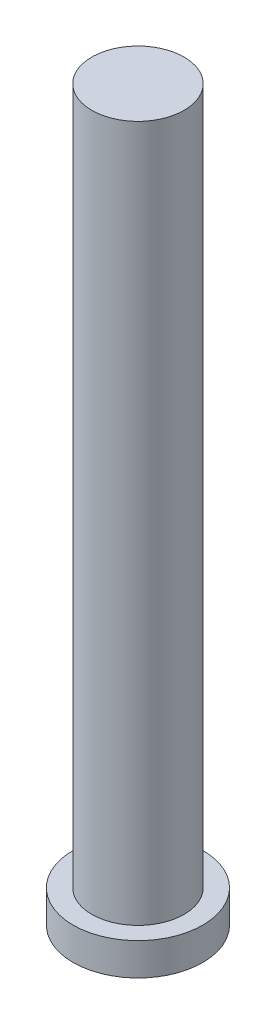
SolidWorks part; units mm, degrees
ref_plane "Front Plane" through (0, 0, 0) normal (0, 0, 1) x (1, 0, 0)
ref_plane "Top Plane" through (0, 0, 0) normal (0, 1, 0) x (1, 0, 0)
ref_plane "Right Plane" through (0, 0, 0) normal (1, 0, 0) x (0, 0, -1)
sketch "Sketch1" plane through (0, 0, 0) normal (0, 1, 0) x (1, 0, 0)
  circle A0 centre (0, 0) radius 4
extrude "Boss-Extrude1" add sketch "Sketch1" along normal blind 2
sketch "Sketch2" plane through (0, 2, 0) normal (0, 1, 0) x (1, 0, 0)
  circle A0 centre (0, 0) radius 2.85
extrude "Boss-Extrude2" add sketch "Sketch2" along normal blind 43
